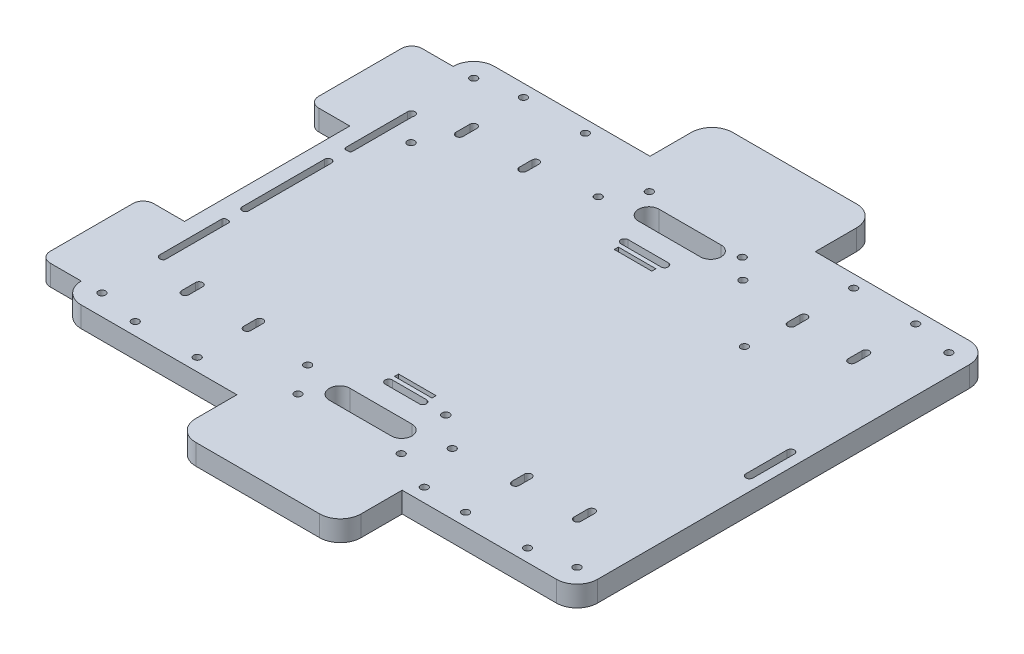
SolidWorks part; units mm, degrees
ref_plane "前视基准面" through (0, 0, 0) normal (0, 0, 1) x (1, 0, 0)
ref_plane "上视基准面" through (0, 0, 0) normal (0, 1, 0) x (1, 0, 0)
ref_plane "右视基准面" through (0, 0, 0) normal (1, 0, 0) x (0, 0, -1)
sketch "草图1" plane through (0, 0, 0) normal (0, 1, 0) x (1, 0, 0)
  line L0 (0.2, 173.5611) -> (0.2, -229.7813) construction
  line L1 (-114.8, 99.9532) -> (-39.4539, 99.9532)
  line L2 (-124.8, 89.9532) -> (-124.8, -90.0468)
  line L3 (-114.8, -100.0468) -> (-39.4539, -100.0468)
  line L4 (125.2, 89.9532) -> (125.2, -90.0468)
  line L7 (-9.7932, 57.9532) -> (9.6378, 57.9532) construction
  line L10 (-9.7932, 59.7032) -> (9.6378, 59.7032)
  line L13 (-9.7932, 56.2032) -> (9.6378, 56.2032)
  line L16 (118.6089, 10) -> (118.6089, -10) construction
  line L18 (-8.0507, -57.9532) -> (8.4507, -57.9532) construction
  line L33 (120.3589, 10) -> (120.3589, -10)
  line L36 (116.8589, 10) -> (116.8589, -10)
  line L39 (-8.0507, -56.2032) -> (8.4507, -56.2032)
  line L54 (-115.05, 60) -> (-115.05, 29) construction
  line L55 (-113.5, 59.1876) -> (-113.5, 30)
  line L56 (-116.8, 60) -> (-116.8, 30)
  line L57 (-8.0507, -59.7032) -> (8.4507, -59.7032)
  line L64 (-94.75, 69.7532) -> (-94.75, 63.0136) construction
  line L68 (-93, 69.7532) -> (-93, 63.0136)
  line L79 (0, 0) -> (207.0532, 0) construction
  line L84 (-96.5, 69.7532) -> (-96.5, 63.0136)
  line L87 (-64.75, 69.7532) -> (-64.75, 63.7371) construction
  line L90 (-63, 69.7532) -> (-63, 63.7371)
  line L96 (-66.5, 69.7532) -> (-66.5, 63.7371)
  line L102 (-64.75, -69.7532) -> (-64.75, -63.7371) construction
  line L107 (-63, -69.7532) -> (-63, -63.7371)
  line L112 (-15.0448, 74.9532) -> (14.9552, 74.9532) construction
  line L117 (-66.5, -69.7532) -> (-66.5, -63.7371)
  line L121 (-94.75, -69.7532) -> (-94.75, -63.0136) construction
  line L124 (-93, -69.7532) -> (-93, -63.0136)
  line L129 (-96.5, -69.7532) -> (-96.5, -63.0136)
  line L132 (65.15, 69.7532) -> (65.15, 63.7371) construction
  line L135 (63.4, 69.7532) -> (63.4, 63.7371)
  line L140 (66.9, 69.7532) -> (66.9, 63.7371)
  line L143 (95.15, 69.7532) -> (95.15, 63.0136) construction
  line L146 (93.4, 69.7532) -> (93.4, 63.0136)
  line L149 (96.9, 69.7532) -> (96.9, 63.0136)
  line L152 (95.15, -69.7532) -> (95.15, -63.0136) construction
  line L155 (93.4, -69.7532) -> (93.4, -63.0136)
  line L160 (-115.8, -29) -> (-114.5, -29)
  line L162 (-116.8, -30) -> (-116.8, -60)
  line L163 (-115.05, -29) -> (-115.05, -60) construction
  line L164 (-113.5, -30) -> (-113.5, -60.8124)
  line L165 (-115.8, 29) -> (-114.5, 29)
  line L169 (96.9, -69.7532) -> (96.9, -63.0136)
  line L172 (65.15, -69.7532) -> (65.15, -63.7371) construction
  line L175 (63.4, -69.7532) -> (63.4, -63.7371)
  line L178 (66.9, -69.7532) -> (66.9, -63.7371)
  line L190 (-15.0448, 79.9532) -> (14.9552, 79.9532)
  line L191 (-15.0448, 69.9532) -> (14.9552, 69.9532)
  line L192 (-39.4539, 99.9532) -> (-39.4539, 119.9532)
  line L193 (-14.8, -74.9532) -> (15.2, -74.9532) construction
  line L194 (-14.8, -79.9532) -> (15.2, -79.9532)
  line L195 (-14.8, -69.9532) -> (15.2, -69.9532)
  line L196 (-115.3275, 20) -> (-115.3275, -20) construction
  line L197 (-113.6775, 20) -> (-113.6775, -20)
  line L198 (-116.9775, 20) -> (-116.9775, -20)
  line L199 (-29.4539, 129.9532) -> (30.5461, 129.9532)
  line L200 (40.5461, 99.9532) -> (40.5461, 119.9532)
  line L201 (40.5461, -100.0468) -> (40.5461, -119.9532)
  line L202 (-39.4539, -100.0468) -> (-39.4539, -119.9532)
  line L203 (-29.4539, -129.9532) -> (30.5461, -129.9532)
  line L204 (40.5461, 99.9532) -> (115.2, 99.9532)
  line L205 (40.5461, -100.0468) -> (115.2, -100.0468)
  line L206 (-124.8, 89.9532) -> (-124.8, 39.9532)
  line L207 (-124.8, 89.9532) -> (-139.8, 89.9532)
  line L208 (-124.8, 39.9532) -> (-139.8, 39.9532)
  line L209 (-144.8, 84.9532) -> (-144.8, 44.9532)
  line L210 (-124.8, -40.0468) -> (-124.8, -90.0468)
  line L211 (-124.8, -40.0468) -> (-139.8, -40.0468)
  line L212 (-124.8, -90.0468) -> (-139.8, -90.0468)
  line L213 (-144.8, -45.0468) -> (-144.8, -85.0468)
  arc A32 (-124.8, 89.9532) -> (-114.8, 99.9532) centre (-114.8, 89.9532) cw
  arc A33 (-114.8, -100.0468) -> (-124.8, -90.0468) centre (-114.8, -90.0468) cw
  arc A34 (125.2, -90.0468) -> (115.2, -100.0468) centre (115.2, -90.0468) cw
  arc A35 (115.2, 99.9532) -> (125.2, 89.9532) centre (115.2, 89.9532) cw
  arc A36 (-113.5, 59.1876) -> (-116.8, 60) centre (-115.05, 60) ccw
  arc A37 (-116.8, -60) -> (-113.5, -60.8124) centre (-115.05, -60) ccw
  circle A87 centre (44.6466, -93.4186) radius 1.75
  circle A97 centre (63.1651, 43) radius 1.75
  circle A101 centre (-103, 47.7923) radius 1.8
  circle A108 centre (-114.8, 89.9532) radius 1.75
  circle A109 centre (-114.8, -90.0468) radius 1.75
  circle A110 centre (115.2, -90.0468) radius 1.75
  circle A111 centre (115.2, 89.9532) radius 1.75
  circle A112 centre (-35, 70.4408) radius 1.75
  circle A113 centre (35, 70.4408) radius 1.75
  circle A118 centre (-34.8, -70.4408) radius 1.75
  circle A119 centre (35.2, -70.4408) radius 1.75
  circle A151 centre (19.6, -57.9532) radius 1.8
  circle A157 centre (25.2, 79.9532) radius 1.75
  circle A158 centre (-24.8, 84.9532) radius 1.75
  circle A159 centre (25, -84.9532) radius 1.75
  circle A160 centre (-25, -84.9532) radius 1.75
  arc A176 (-114.5, 29) -> (-113.5, 30) centre (-114.5, 30) ccw
  arc A177 (-115.8, 29) -> (-116.8, 30) centre (-115.8, 30) cw
  arc A178 (-116.8, -30) -> (-115.8, -29) centre (-115.8, -30) cw
  arc A179 (-114.5, -29) -> (-113.5, -30) centre (-114.5, -30) cw
  arc A186 (-15.0448, 79.9532) -> (-15.0448, 69.9532) centre (-15.0448, 74.9532) ccw
  arc A187 (14.9552, 69.9532) -> (14.9552, 79.9532) centre (14.9552, 74.9532) ccw
  arc A188 (-14.8, -79.9532) -> (-14.8, -69.9532) centre (-14.8, -74.9532) cw
  arc A189 (15.2, -69.9532) -> (15.2, -79.9532) centre (15.2, -74.9532) cw
  arc A190 (-113.6775, 20) -> (-116.9775, 20) centre (-115.3275, 20) ccw
  arc A191 (-116.9775, -20) -> (-113.6775, -20) centre (-115.3275, -20) ccw
  arc A192 (120.3589, 10) -> (116.8589, 10) centre (118.6089, 10) ccw
  arc A193 (116.8589, -10) -> (120.3589, -10) centre (118.6089, -10) ccw
  arc A194 (-39.4539, 119.9532) -> (-29.4539, 129.9532) centre (-29.4539, 119.9532) cw
  arc A195 (40.5461, 119.9532) -> (30.5461, 129.9532) centre (30.5461, 119.9532) ccw
  arc A196 (40.5461, -119.9532) -> (30.5461, -129.9532) centre (30.5461, -119.9532) cw
  arc A197 (-39.4539, -119.9532) -> (-29.4539, -129.9532) centre (-29.4539, -119.9532) ccw
  arc A198 (-139.8, -90.0468) -> (-144.8, -85.0468) centre (-139.8, -85.0468) cw
  arc A199 (-144.8, -45.0468) -> (-139.8, -40.0468) centre (-139.8, -45.0468) cw
  arc A200 (-139.8, 39.9532) -> (-144.8, 44.9532) centre (-139.8, 44.9532) cw
  arc A201 (-139.8, 89.9532) -> (-144.8, 84.9532) centre (-139.8, 84.9532) ccw
  circle A202 centre (-94.75, 93.9532) radius 1.75
  circle A203 centre (-64.75, 93.9532) radius 1.75
  circle A208 centre (-64.75, -93.9532) radius 1.75
  circle A209 centre (-94.75, -93.9532) radius 1.75
  circle A210 centre (95.15, -93.9532) radius 1.75
  circle A211 centre (65.15, -93.9532) radius 1.75
  circle A215 centre (95.15, 93.9532) radius 1.75
  circle A216 centre (65.15, 93.9532) radius 1.75
  arc A219 (-9.7932, 59.7032) -> (-9.7932, 56.2032) centre (-9.7932, 57.9532) ccw
  arc A220 (9.6378, 56.2032) -> (9.6378, 59.7032) centre (9.6378, 57.9532) ccw
  arc A221 (-8.0507, -56.2032) -> (-8.0507, -59.7032) centre (-8.0507, -57.9532) ccw
  arc A222 (8.4507, -59.7032) -> (8.4507, -56.2032) centre (8.4507, -57.9532) ccw
  arc A223 (-93, 69.7532) -> (-96.5, 69.7532) centre (-94.75, 69.7532) ccw
  arc A224 (-96.5, 63.0136) -> (-93, 63.0136) centre (-94.75, 63.0136) ccw
  arc A225 (-63, 69.7532) -> (-66.5, 69.7532) centre (-64.75, 69.7532) ccw
  arc A226 (-66.5, 63.7371) -> (-63, 63.7371) centre (-64.75, 63.7371) ccw
  arc A227 (-63, -69.7532) -> (-66.5, -69.7532) centre (-64.75, -69.7532) cw
  arc A228 (-66.5, -63.7371) -> (-63, -63.7371) centre (-64.75, -63.7371) cw
  arc A229 (-93, -69.7532) -> (-96.5, -69.7532) centre (-94.75, -69.7532) cw
  arc A230 (-96.5, -63.0136) -> (-93, -63.0136) centre (-94.75, -63.0136) cw
  circle A231 centre (-64.75, -93.9532) radius 1.75
  circle A232 centre (-94.75, -93.9532) radius 1.75
  arc A233 (63.4, 69.7532) -> (66.9, 69.7532) centre (65.15, 69.7532) cw
  arc A234 (66.9, 63.7371) -> (63.4, 63.7371) centre (65.15, 63.7371) cw
  arc A235 (93.4, 69.7532) -> (96.9, 69.7532) centre (95.15, 69.7532) cw
  arc A236 (96.9, 63.0136) -> (93.4, 63.0136) centre (95.15, 63.0136) cw
  arc A237 (93.4, -69.7532) -> (96.9, -69.7532) centre (95.15, -69.7532) ccw
  arc A238 (96.9, -63.0136) -> (93.4, -63.0136) centre (95.15, -63.0136) ccw
  arc A239 (63.4, -69.7532) -> (66.9, -69.7532) centre (65.15, -69.7532) ccw
  arc A240 (66.9, -63.7371) -> (63.4, -63.7371) centre (65.15, -63.7371) ccw
  circle A241 centre (95.15, -93.9532) radius 1.75
  circle A242 centre (65.15, -93.9532) radius 1.75
  circle A243 centre (65.15, 93.9532) radius 1.75
  circle A244 centre (95.15, 93.9532) radius 1.75
  point P20 (65.15, 66.7452)
  point P31 (95.15, 66.3834)
  point P32 (-94.75, 66.3834)
  point P39 (-0.0777, 57.9532)
  point P44 (118.6089, 0)
  point P47 (0.2, -57.9532)
  point P58 (-64.75, 66.7452)
  point P65 (-64.75, -66.7452)
  point P71 (-94.75, -66.3834)
  point P84 (95.15, -66.3834)
  point P91 (65.15, -66.7452)
  point P128 (-115.05, 0)
  point P176 (-103, 47.7923)
  point P196 (44.6466, -93.4186)
  point P218 (60.6475, 42.9532)
  point P246 (19.6, 19.6)
  point P267 (-0.0448, 74.9532)
  point P303 (-115.3275, 0)
  point P304 (-115.05, 0)
  point P382 (0.2, -74.9532)
  point P389 (-115.3275, 0)
  point P394 (-39.4539, 129.9532)
  point P397 (40.5461, 129.9532)
  dimension "D11" = 22
  dimension "D13" = 30
  dimension "D16" = 10
  dimension "D17" = 10
  dimension "D18" = 10
  dimension "D19" = 10
  dimension "D14" = 1.75
  dimension "D25" = 50
  dimension "D23" = 50
  dimension "D24" = 22
  dimension "D43" = 3.5
  dimension "D44" = 3.5
  dimension "D45" = 3.5
  dimension "D46" = 3.5
  dimension "D38" = 3.5
  dimension "D39" = 80
  dimension "D41" = 24.2
  dimension "D47" = 3.5
  dimension "D49" = 3.5
  dimension "D58" = 3.5
  dimension "D59" = 3.5
  dimension "D12" = 30
  dimension "D71" = 3.5
  dimension "D72" = 3.6
  dimension "D73" = 3.5
  dimension "D82" = 1
  dimension "D83" = 1
  dimension "D84" = 1
  dimension "D85" = 10
  dimension "D86" = 80
  dimension "D98" = 10
  dimension "D99" = 10
  dimension "D104" = 5
  dimension "D35" = 30
  dimension "D2" = 8
  dimension "D15" = 120
  dimension "D20" = 230
  dimension "D21" = 180
  dimension "D22" = 3.3
  dimension "D60" = 21.8
  dimension "D76" = 3.3
  dimension "D77" = 3.3
  dimension "D78" = 15
  dimension "D79" = 20
  dimension "D89" = 30
  dimension "D90" = 30
  dimension "D91" = 10
  dimension "D92" = 20
  dimension "D93" = 20
  dimension "D94" = 3.5
  dimension "D95" = 20
  dimension "D96" = 80
  dimension "D97" = 30
  dimension "D100" = 6
extrude "凸台-拉伸1" add sketch "草图1" along normal blind 10
sketch "草图2" plane through (0, 10, 0) normal (0, 1, 0) x (1, 0, 0)
  line L0 (-9.0228, -54.2032) -> (9.1324, -54.2032)
  line L1 (-9.0228, -54.2032) -> (-9.0228, -52.2032)
  line L2 (9.1324, -54.2032) -> (9.1324, -52.2032)
  line L3 (-9.0228, -52.2032) -> (9.1324, -52.2032)
  line L4 (-8.0507, -56.2032) -> (8.4507, -56.2032) construction
  line L5 (-9.0228, 54.2032) -> (9.1324, 54.2032)
  line L6 (-9.0228, 54.2032) -> (-9.0228, 52.2032)
  line L7 (9.1324, 54.2032) -> (9.1324, 52.2032)
  line L8 (-9.0228, 52.2032) -> (9.1324, 52.2032)
  line L9 (-9.7932, 56.2032) -> (9.6378, 56.2032) construction
  dimension "D1" = 2
  dimension "D2" = 2
extrude "切除-拉伸1" cut sketch "草图2" against normal blind 10
